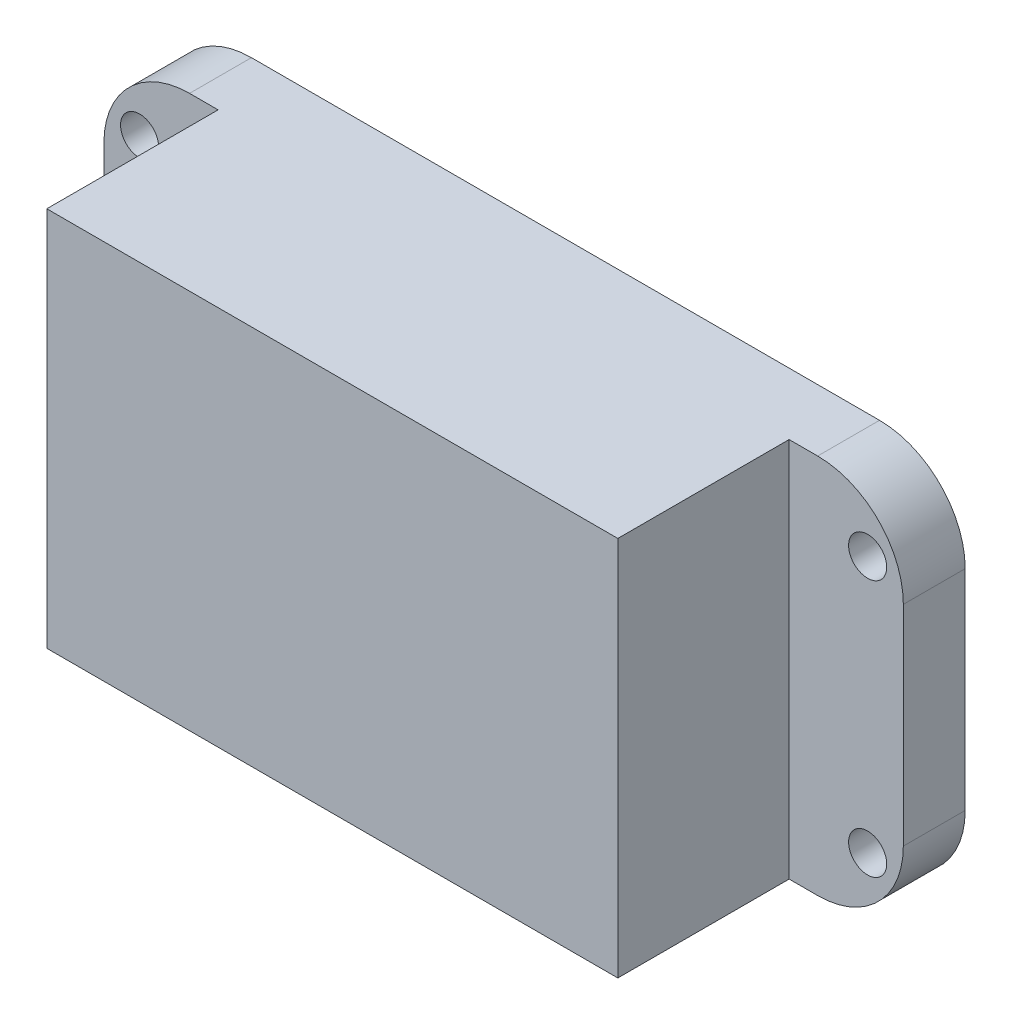
SolidWorks part; units mm, degrees
material "ABS"
ref_plane "正面" through (0, 0, 0) normal (0, 0, 1) x (1, 0, 0)
ref_plane "平面" through (0, 0, 0) normal (0, 1, 0) x (1, 0, 0)
ref_plane "右側面" through (0, 0, 0) normal (1, 0, 0) x (0, 0, -1)
sketch "ｽｹｯﾁ1" plane through (0, 0, 0) normal (0, 0, 1) x (1, 0, 0)
  line L0 (0, 20) -> (0, 0) construction
  line L1 (33, -20) -> (-33, -20)
  line L2 (42, -11) -> (42, 11)
  line L3 (33, 20) -> (-33, 20)
  line L4 (-42, -11) -> (-42, 11)
  line L5 (42, -20) -> (-42, 20) construction
  line L6 (42, 20) -> (-42, -20) construction
  line L7 (0, 0) -> (-42, 0) construction
  arc A0 (42, 11) -> (33, 20) centre (33, 11) ccw
  arc A1 (33, -20) -> (42, -11) centre (33, -11) ccw
  arc A2 (-33, -20) -> (-42, -11) centre (-33, -11) cw
  arc A3 (-33, 20) -> (-42, 11) centre (-33, 11) ccw
  circle A4 centre (-38.25, 13.5) radius 2
  circle A5 centre (38.25, 13.5) radius 2
  circle A6 centre (38.25, -13.5) radius 2
  circle A7 centre (-38.25, -13.5) radius 2
  point P0 (0, 0)
  dimension "D3" = 9
  dimension "D4" = 4
  dimension "D1" = 40
  dimension "D2" = 84
  dimension "D5" = 27
  dimension "D6" = 76.5
extrude "ﾎﾞｽ - 押し出し1" add sketch "ｽｹｯﾁ1" along normal blind 6.5
sketch "ｽｹｯﾁ2" plane through (0, 0, 6.5) normal (0, 0, 1) x (1, 0, 0)
  line L0 (-33, -20) -> (33, -20) construction
  line L1 (30, 20) -> (-30, 20)
  line L2 (30, 20) -> (30, -20)
  line L3 (30, -20) -> (-30, -20)
  line L4 (-30, 20) -> (-30, -20)
  line L5 (30, 20) -> (-30, -20) construction
  line L6 (30, -20) -> (-30, 20) construction
  point P0 (0, 0)
  dimension "D1" = 60
extrude "ﾎﾞｽ - 押し出し2" add sketch "ｽｹｯﾁ2" along normal blind 18
